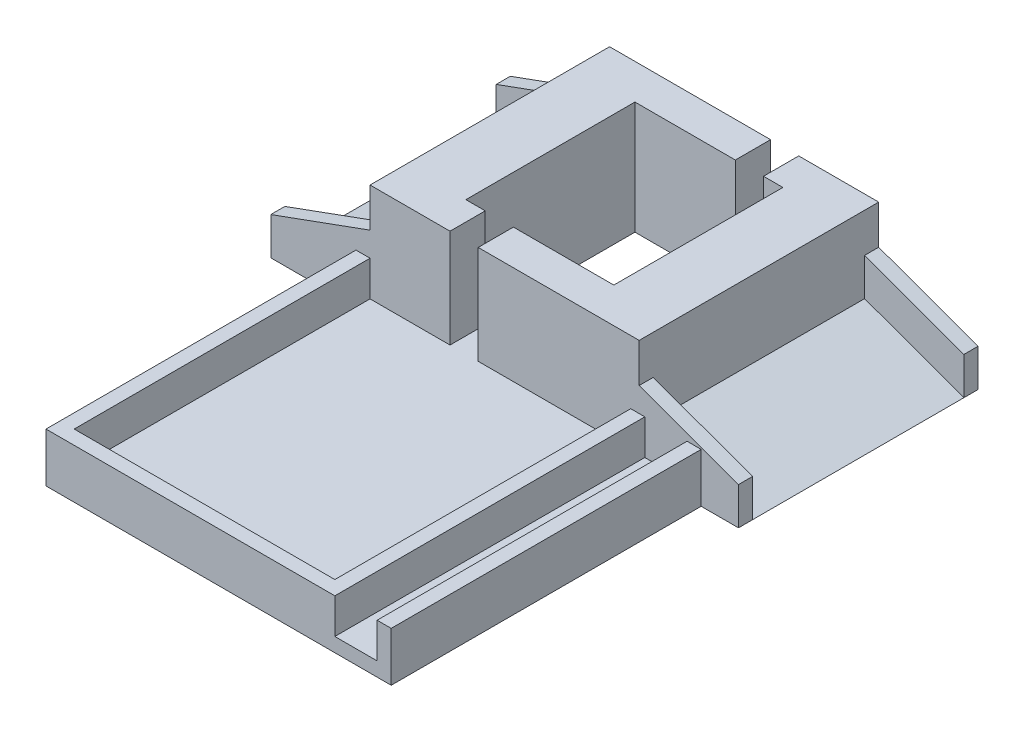
SolidWorks part; units mm, degrees
ref_plane "Front Plane" through (0, 0, 0) normal (0, 0, 1) x (1, 0, 0)
ref_plane "Top Plane" through (0, 0, 0) normal (0, 1, 0) x (1, 0, 0)
ref_plane "Right Plane" through (0, 0, 0) normal (1, 0, 0) x (0, 0, -1)
ref_plane "Plane2" through (19.1, 0, 0) normal (1, 0, 0) x (0, 0, -1)
sketch "Sketch4" plane through (0, 0, 0) normal (0, 0, 1) x (1, 0, 0)
  line L0 (0, 0) -> (-14.0954, 0)
  line L1 (-14.0954, 0) -> (0, 5.1303)
  line L2 (0, 5.1303) -> (0, 0)
  line L3 (19.1, -55) -> (19.1, 55) construction
  line L4 (52.2954, 0) -> (38.2, 5.1303)
  line L5 (38.2, 0) -> (52.2954, 0)
  line L6 (38.2, 5.1303) -> (38.2, 0)
  dimension "D1" = 15
  dimension "D2" = 20
extrude "Boss-Extrude1" add sketch "Sketch4" along normal blind 34
sketch "Sketch5" plane through (0, 0, 0) normal (0, 1, 0) x (1, 0, 0)
  line L10 (0, 0) -> (38.2, 0)
  line L11 (0, 0) -> (0, -34)
  line L12 (0, -34) -> (38.2, -34)
  line L13 (38.2, 0) -> (38.2, -34)
extrude "Boss-Extrude2" add sketch "Sketch5" along normal blind 16
ref_plane "Plane5" through (-12.4465, -4.5302, 0) normal (0.9397, 0.342, 0) x (0, 0, -1)
sketch "Sketch12" plane through (-12.4465, -4.5302, 0) normal (0.9397, 0.342, 0) x (0, 0, -1)
  line L1 (0, 4.8209) -> (-2, 4.8209)
  line L2 (0, 4.8209) -> (0, 9.8209)
  line L3 (0, 9.8209) -> (-2, 9.8209)
  line L4 (-2, 4.8209) -> (-2, 9.8209)
  line L5 (-34, 4.8209) -> (-32, 4.8209)
  line L6 (-34, 4.8209) -> (-34, 9.8209)
  line L7 (-34, 9.8209) -> (-32, 9.8209)
  line L8 (-32, 4.8209) -> (-32, 9.8209)
  dimension "D1" = 2
  dimension "D2" = 5
  dimension "D3" = 2
  dimension "D4" = 5
extrude "Boss-Extrude7" add sketch "Sketch12" along normal up to surface (15 mm away)
ref_plane "Plane6" through (46.178, -16.8074, 0) normal (0.9397, -0.342, 0) x (0, 0, -1)
sketch "Sketch13" plane through (46.178, -16.8074, 0) normal (0.9397, -0.342, 0) x (0, 0, -1)
  line L1 (-34, 17.8861) -> (-32, 17.8861)
  line L2 (-34, 17.8861) -> (-34, 22.8861)
  line L3 (-34, 22.8861) -> (-32, 22.8861)
  line L4 (-32, 17.8861) -> (-32, 22.8861)
  line L5 (0, 17.8861) -> (-2, 17.8861)
  line L6 (0, 17.8861) -> (0, 22.8861)
  line L7 (0, 22.8861) -> (-2, 22.8861)
  line L8 (-2, 17.8861) -> (-2, 22.8861)
  dimension "D1" = 2
  dimension "D2" = 5
  dimension "D3" = 2
  dimension "D4" = 5
extrude "Boss-Extrude8" add sketch "Sketch13" against normal up to surface (15 mm away)
sketch "Sketch6" plane through (0, 0, 0) normal (0, 1, 0) x (1, 0, 0)
  line L1 (11.35, -29) -> (15.35, -29)
  line L2 (11.35, -29) -> (11.35, -34)
  line L3 (11.35, -34) -> (15.35, -34)
  line L4 (15.35, -29) -> (15.35, -34)
  line L7 (22.85, -5) -> (26.85, -5)
  line L8 (22.85, -5) -> (22.85, 0)
  line L9 (22.85, 0) -> (26.85, 0)
  line L10 (26.85, -5) -> (26.85, 0)
  line L11 (38.2, 0) -> (0, 0) construction
  line L12 (19.1, -8.8) -> (19.1, 8.8) construction
  line L13 (-14.0954, -34) -> (52.2954, -34) construction
  dimension "D1" = 4
  dimension "D2" = 4
  dimension "D3" = 7.5
  dimension "D4" = 3.75
  dimension "D5" = 5
  dimension "D6" = 5
extrude "Cut-Extrude1" cut sketch "Sketch6" along direction (0, 1, 0) on the side of the normal up to surface (14 mm away) from offset 2
sketch "Sketch7" plane through (0, 0, 0) normal (0, 1, 0) x (1, 0, 0)
  line L1 (-2, -34) -> (47, -34)
  line L2 (-2, -34) -> (-2, -78)
  line L3 (-2, -78) -> (47, -78)
  line L4 (47, -34) -> (47, -78)
  dimension "D1" = 44
  dimension "D2" = 49
extrude "Boss-Extrude3" add sketch "Sketch7" along normal blind 2
ref_plane "Plane3" through (0, 0, 78) normal (0, 0, 1) x (1, 0, 0)
sketch "Sketch8" plane through (0, 0, 78) normal (0, 0, 1) x (1, 0, 0)
  line L1 (47, 2) -> (37, 2)
  line L2 (47, 2) -> (47, 7)
  line L3 (47, 7) -> (37, 7)
  line L4 (37, 2) -> (37, 7)
  line L5 (-2, 2) -> (0, 2)
  line L6 (-2, 2) -> (-2, 7)
  line L7 (-2, 7) -> (0, 7)
  line L8 (0, 2) -> (0, 7)
  dimension "D1" = 10
  dimension "D2" = 5
  dimension "D3" = 2
  dimension "D4" = 5
extrude "Boss-Extrude5" add sketch "Sketch8" against normal blind 45
sketch "Sketch9" plane through (0, 7, 0) normal (0, 1, 0) x (1, 0, 0)
  line L1 (39, -34) -> (45, -34)
  line L2 (39, -34) -> (39, -78)
  line L3 (39, -78) -> (45, -78)
  line L4 (45, -34) -> (45, -78)
  line L5 (-18.3223, -78) -> (18.3223, -78) construction
  line L6 (37, -34) -> (37, -78) construction
  line L7 (37, -34) -> (47, -34) construction
  dimension "D1" = 6
  dimension "D2" = 2
extrude "Cut-Extrude2" cut sketch "Sketch9" against normal up to surface and the other way up to surface up to face at (15.925, 2, 43.75) other way up to face at (46.1027, 7.5748, 33)
sketch "Sketch10" plane through (0, 16, 0) normal (0, 1, 0) x (1, 0, 0)
  line L0 (15.35, -29) -> (11.35, -29) construction
  line L6 (22.85, -5) -> (26.85, -5) construction
  line L7 (8.6, -5) -> (29.6, -5)
  line L8 (8.6, -5) -> (8.6, -29)
  line L9 (8.6, -29) -> (29.6, -29)
  line L10 (29.6, -5) -> (29.6, -29)
  line L11 (19.1, -8.8) -> (19.1, 8.8) construction
  point P9 (19.1, -5)
  dimension "D1" = 21
extrude "Cut-Extrude3" cut sketch "Sketch10" against normal up to surface (16 mm away) up to face at (20.2333, 0, 30)
sketch "Sketch11" plane through (0, 0, 0) normal (1, 0, 0) x (0, 0, -1)
  line L0 (-78, 18.3223) -> (-78, -18.3223) construction
  line L1 (-78, 7) -> (-76, 7)
  line L2 (-78, 7) -> (-78, 2)
  line L3 (-78, 2) -> (-76, 2)
  line L4 (-76, 7) -> (-76, 2)
  line L5 (-34, 2) -> (-78, 2) construction
  dimension "D1" = 2
extrude "Boss-Extrude6" add sketch "Sketch11" along normal up to surface (37 mm away) up to face at (37, 4.5, 56)
sketch "Sketch14" plane through (0, 0, 0) normal (0, 1, 0) x (1, 0, 0)
  line L1 (-14.0954, 0) -> (-19.0954, 0)
  line L2 (-14.0954, 0) -> (-14.0954, -34)
  line L3 (-14.0954, -34) -> (-19.0954, -34)
  line L4 (-19.0954, 0) -> (-19.0954, -34)
  line L5 (52.2954, 0) -> (57.2954, 0)
  line L6 (52.2954, 0) -> (52.2954, -34)
  line L7 (52.2954, -34) -> (57.2954, -34)
  line L8 (57.2954, 0) -> (57.2954, -34)
  dimension "D1" = 5
  dimension "D2" = 5
extrude "Cut-Extrude4" cut sketch "Sketch14" along normal up to surface (16 mm away)
